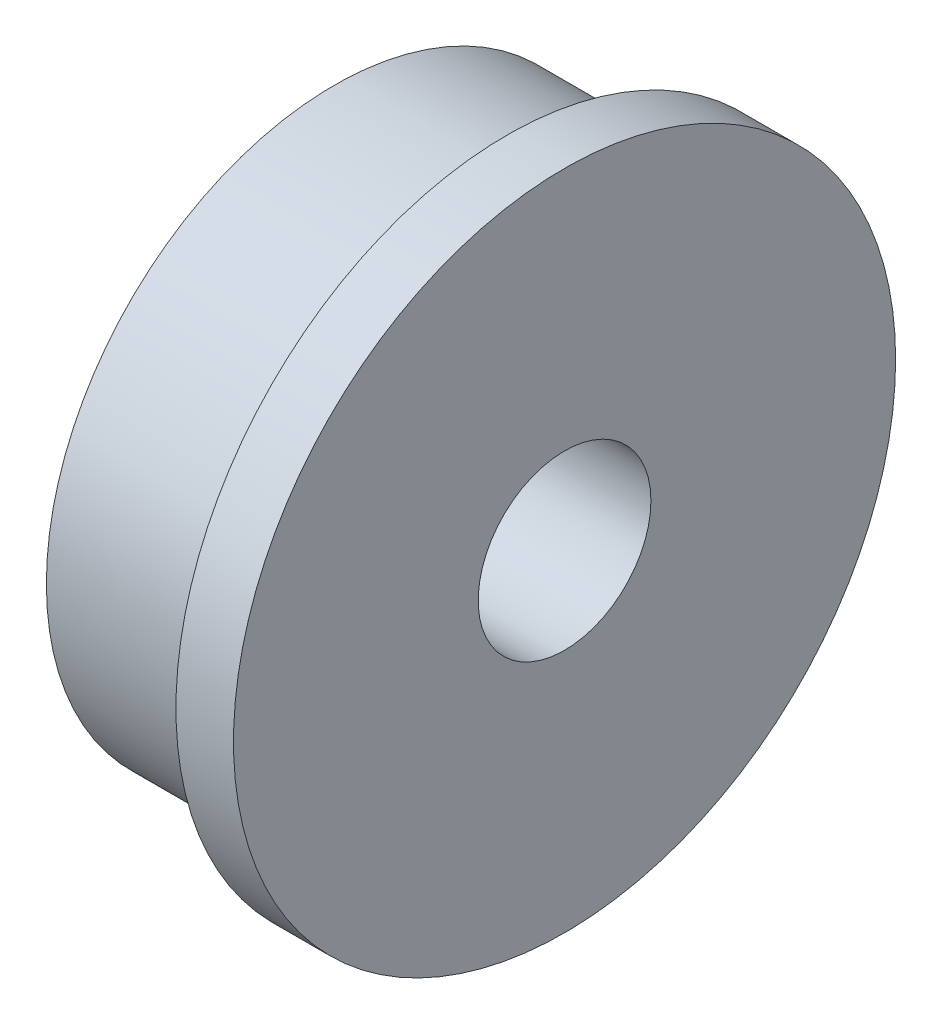
SolidWorks part; units mm, degrees
ref_plane "前视基准面" through (0, 0, 0) normal (0, 0, 1) x (1, 0, 0)
ref_plane "上视基准面" through (0, 0, 0) normal (0, 1, 0) x (1, 0, 0)
ref_plane "右视基准面" through (0, 0, 0) normal (1, 0, 0) x (0, 0, -1)
sketch "草图2" plane through (0, 0, 0) normal (0, 0, 1) x (1, 0, 0)
  line L0 (0, 0) -> (-30.7149, 0) construction
  line L1 (-5.1435, 1.5) -> (-9.1435, 1.5)
  line L2 (-9.1435, 1.5) -> (-9.1435, 5)
  line L3 (-9.1435, 5) -> (-6.1435, 5)
  line L4 (-6.1435, 5) -> (-6.1435, 5.75)
  line L5 (-6.1435, 5.75) -> (-5.1435, 5.75)
  line L6 (-5.1435, 5.75) -> (-5.1435, 1.5)
  dimension "D1" = 3
  dimension "D2" = 10
  dimension "D3" = 11.5
  dimension "D4" = 4
  dimension "D5" = 1
revolve "旋转1" add sketch "草图2" angle 360 about L0
